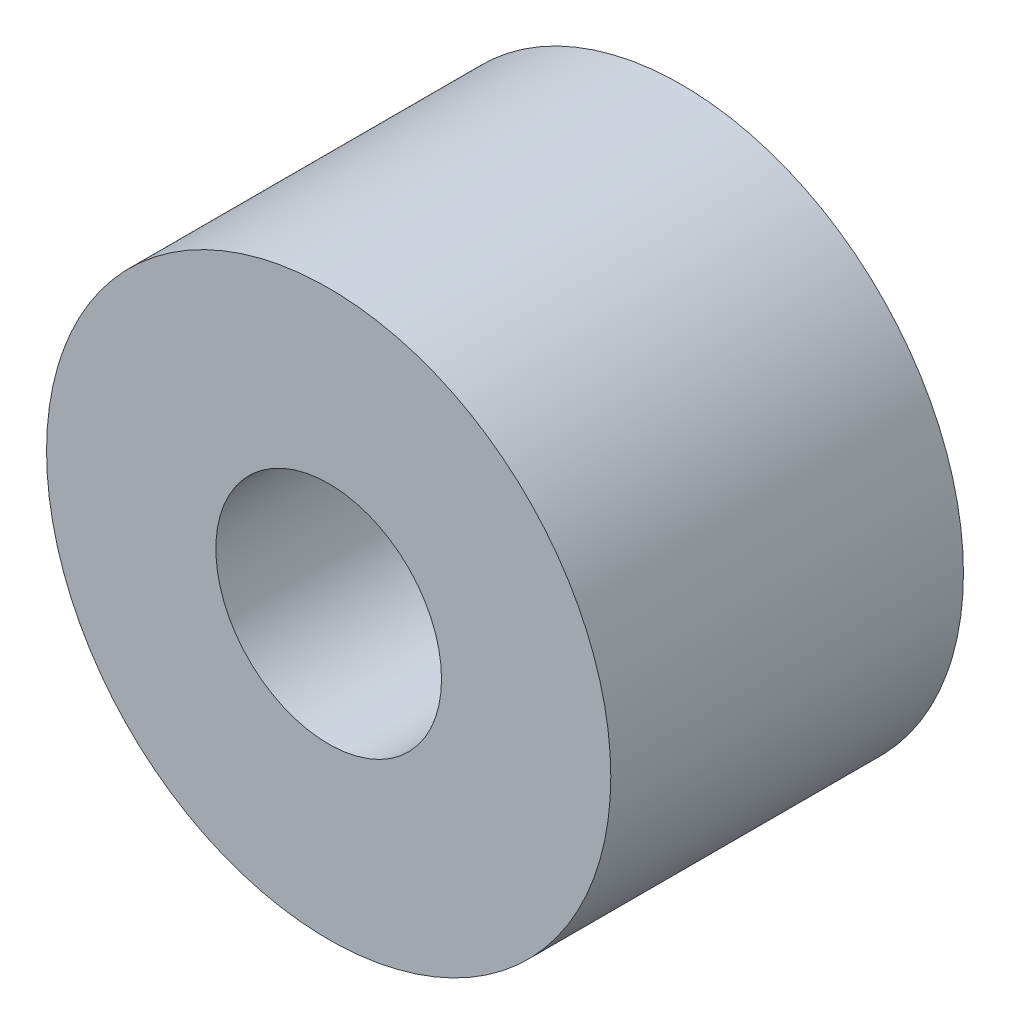
SolidWorks part; units mm, degrees
ref_plane "Front Plane" through (0, 0, 0) normal (0, 0, 1) x (1, 0, 0)
ref_plane "Top Plane" through (0, 0, 0) normal (0, 1, 0) x (1, 0, 0)
ref_plane "Right Plane" through (0, 0, 0) normal (1, 0, 0) x (0, 0, -1)
sketch "Sketch1" plane through (0, 0, 0) normal (0, 0, 1) x (1, 0, 0)
  line L0 (0, 1.6) -> (0, 4) construction
  line L1 (0, -1.6) -> (0, -4) construction
  circle A0 centre (0, 0) radius 4
  circle A1 centre (0, 0) radius 1.6
  dimension "OD" = 8
  dimension "ID" = 3.2
sketch "Sketch2" plane through (0, 0, 0) normal (1, 0, 0) x (0, 0, -1)
  line L0 (-2.5, 1.6) -> (2.5, 1.6) construction
  line L1 (-2.5, -1.6) -> (2.5, -1.6) construction
  line L2 (-2.5, -4) -> (2.5, -4) construction
  line L3 (-2.5, 4) -> (2.5, 4) construction
  dimension "Length" = 5
extrude "Extrude1" add sketch "Sketch1" along normal up to vertex (2.5 mm away) and the other way up to vertex (2.5 mm away) up to point (0, 1.6, 2.5) other way up to point (0, 1.6, -2.5)
sketch "Sketch3" plane through (0, 0, 2.5) normal (0, 0, 1) x (1, 0, 0)
  circle A0 centre (0, 0) radius 1.6 construction
  circle A3 centre (0, 0) radius 1.6
  point P3 (-1.6, 0)
